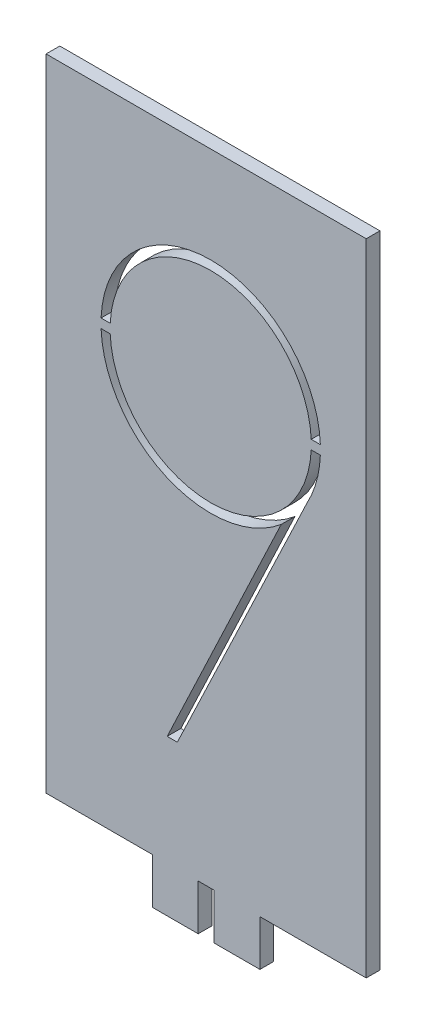
SolidWorks part; units mm, degrees
material "Glas"
ref_plane "Ebene vorne" through (0, 0, 0) normal (0, 0, 1) x (1, 0, 0)
ref_plane "Ebene oben" through (0, 0, 0) normal (0, 1, 0) x (1, 0, 0)
ref_plane "Ebene rechts" through (0, 0, 0) normal (1, 0, 0) x (0, 0, -1)
sketch "Skizze1" plane through (0, 0, 0) normal (0, 0, 1) x (1, 0, 0)
  line L1 (0, 0) -> (35, 0)
  line L2 (0, 0) -> (0, 75)
  line L3 (0, 75) -> (35, 75)
  line L4 (35, 0) -> (35, 75)
  dimension "D1" = 35
  dimension "D2" = 75
extrude "Aufsatz-Linear austragen1" add sketch "Skizze1" along normal blind 1.5
sketch "Skizze2" plane through (0, 0, 1.5) normal (0, 0, 1) x (1, 0, 0)
  line L0 (0, 0) -> (35, 0) construction
  line L1 (0, 0) -> (11.63, 0)
  line L2 (0, 0) -> (0, 5)
  line L3 (0, 5) -> (11.63, 5)
  line L4 (11.63, 0) -> (11.63, 5)
  line L5 (23.38, 5) -> (35, 5)
  line L6 (23.38, 5) -> (23.38, 0)
  line L7 (23.38, 0) -> (35, 0)
  line L8 (35, 5) -> (35, 0)
  line L9 (16.63, 0) -> (18.38, 0)
  line L10 (16.63, 0) -> (16.63, 5)
  line L11 (16.63, 5) -> (18.38, 5)
  line L12 (18.38, 0) -> (18.38, 5)
  dimension "D1" = 5
  dimension "D2" = 5
  dimension "D3" = 5
  dimension "D4" = 11.63
  dimension "D5" = 1.75
  dimension "D6" = 5
extrude "Schnitt-Linear austragen1" cut sketch "Skizze2" against normal blind 1.5
sketch "Skizze13" plane through (0, 0, 1.5) normal (0, 0, 1) x (1, 0, 0)
  line L0 (35, 75) -> (0, 75) construction
  line L1 (35, 5) -> (35, 75) construction
  circle A0 centre (18, 52.5) radius 11
  circle A1 centre (18, 52.5) radius 12
  dimension "D1" = 24
  dimension "D2" = 22
  dimension "D5" = 24
  dimension "D6" = 22
  dimension "D3" = 22.5
  dimension "D4" = 17
extrude "Schnitt-Linear austragen10" cut sketch "Skizze13" against normal blind 20
sketch "Skizze14" plane through (0, 0, 1.5) normal (0, 0, 1) x (1, 0, 0)
  line L0 (35, 75) -> (0, 75) construction
  line L1 (4.7872, 53) -> (31.9933, 53)
  line L2 (4.7872, 53) -> (4.7872, 52)
  line L3 (4.7872, 52) -> (31.9933, 52)
  line L4 (31.9933, 53) -> (31.9933, 52)
  dimension "D1" = 1
  dimension "D2" = 22
extrude "Aufsatz-Linear austragen2" add sketch "Skizze14" against normal blind 1.5
sketch "Skizze15" plane through (0, 0, 1.5) normal (0, 0, 1) x (1, 0, 0)
  line L1 (14.3478, 17) -> (13.2412, 17)
  line L2 (13.2412, 17) -> (27.2316, 46.5185)
  line L3 (27.2316, 46.5185) -> (29.4062, 48.7718)
  line L4 (11.63, 5) -> (0, 5) construction
  line L5 (14.3478, 17) -> (28.5323, 46.7494)
  line L6 (28.5323, 46.7494) -> (29.2835, 48.4157)
  line L7 (29.2835, 48.4157) -> (29.4062, 48.7718)
  arc A0 (6.0104, 52) -> (29.9896, 52) centre (18, 52.5) ccw construction
  arc A1 (7.0114, 52) -> (28.9886, 52) centre (18, 52.5) ccw construction
  dimension "D3" = 3.2282
  dimension "D2" = 12
extrude "Schnitt-Linear austragen11" cut sketch "Skizze15" against normal blind 20
